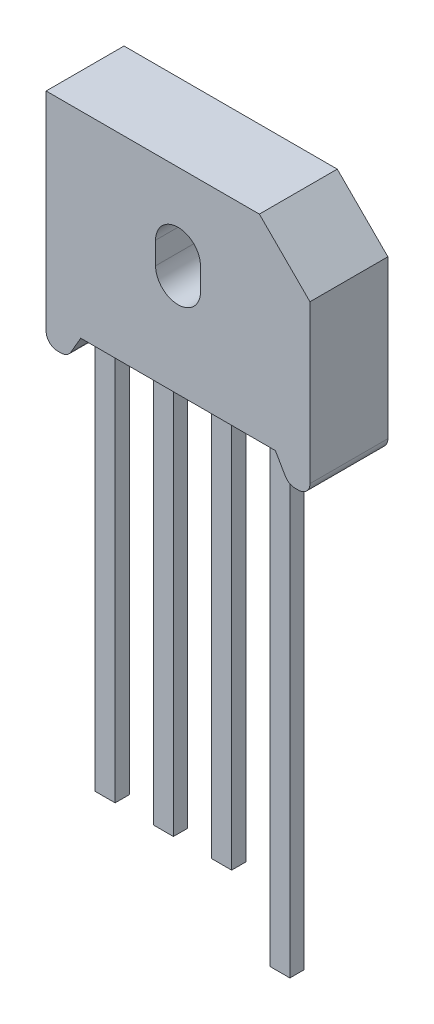
SolidWorks part; units mm, degrees
ref_plane "Front Plane" through (0, 0, 0) normal (0, 0, 1) x (1, 0, 0)
ref_plane "Top Plane" through (0, 0, 0) normal (0, 1, 0) x (1, 0, 0)
ref_plane "Right Plane" through (0, 0, 0) normal (1, 0, 0) x (0, 0, -1)
sketch "Sketch1" plane through (0, 0, 0) normal (0, 0, 1) x (1, 0, 0)
  line L0 (0, 47.902) -> (0, -49.3492) construction
  line L1 (-55.8616, 0) -> (48.9151, 0) construction
  line L2 (-11.6, 14.4039) -> (-11.6, -2.8961)
  line L6 (-11.6, 14.4039) -> (11.6, 14.4039)
  line L9 (11.6, 14.4039) -> (11.6, -2.8961)
  line L10 (7.15, 14.4039) -> (11.6, 9.9539)
  line L11 (0, 7.8539) -> (0, 5.9039) construction
  line L12 (1.975, 7.8539) -> (1.975, 5.9039)
  line L13 (-1.975, 7.8539) -> (-1.975, 5.9039)
  line L14 (-11.6, -2.8961) -> (-11.6, -3.8961)
  line L15 (-10.6, -4.8961) -> (-10.2891, -4.8961)
  line L16 (-9.4231, -4.3961) -> (-8.5588, -2.8991)
  line L17 (-8.5588, -2.8991) -> (8.5588, -2.8991)
  line L18 (11.6, -2.8961) -> (11.6, -3.8961)
  line L19 (10.6, -4.8961) -> (10.2891, -4.8961)
  line L20 (9.4231, -4.3961) -> (8.5588, -2.8991)
  arc A0 (1.975, 7.8539) -> (-1.975, 7.8539) centre (0, 7.8539) ccw
  arc A1 (-1.975, 5.9039) -> (1.975, 5.9039) centre (0, 5.9039) ccw
  arc A2 (9.4231, -4.3961) -> (10.2891, -4.8961) centre (10.2891, -3.8961) ccw
  arc A3 (-9.4231, -4.3961) -> (-10.2891, -4.8961) centre (-10.2891, -3.8961) cw
  arc A4 (-11.6, -3.8961) -> (-10.6, -4.8961) centre (-10.6, -3.8961) ccw
  arc A5 (11.6, -3.8961) -> (10.6, -4.8961) centre (10.6, -3.8961) cw
  point P7 (-8.564, -3.1175)
  point P12 (0, 14.4039)
  point P13 (0, -9.3053)
  point P19 (0, 6.8789)
  point P28 (0, -2.8991)
  point P30 (9.7118, -4.8961)
  point P33 (-9.7118, -4.8961)
  point P36 (-11.6, -4.8961)
  point P39 (11.6, -4.8961)
  point P40 (11.6, 10.1587)
  dimension "D8" = 1
  dimension "D9" = 1
  dimension "D1" = 23.2
  dimension "D2" = 3.95
  dimension "D3" = 1.95
  dimension "D4" = 17.3
  dimension "D5" = 19.3
  dimension "D6" = 240
  dimension "D7" = 10.8
  dimension "D10" = 4.45
  dimension "D11" = 135
extrude "Boss-Extrude1" add sketch "Sketch1" along normal mid plane 6.85 contours A5 L18 L9 L10 L6 L2 L14 A4 L15 A3 L16 L17 L20 A2 L19 A1 L13 A0 L12
sketch "Sketch2" plane through (0, -2.8991, 0) normal (0, -1, 0) x (1, 0, 0)
  line L0 (-7.9995, 1.525) -> (8.0463, 1.525) construction
  line L1 (-8.5588, -3.425) -> (8.5588, -3.425) construction
  line L2 (-8.5588, 0.9) -> (-6.8088, 0.9)
  line L3 (-8.5588, 0.9) -> (-8.5588, 2.15)
  line L4 (-8.5588, 2.15) -> (-6.8088, 2.15)
  line L5 (-6.8088, 0.9) -> (-6.8088, 2.15)
  line L6 (-8.5588, 0.9) -> (-6.8088, 2.15) construction
  line L7 (-8.5588, 2.15) -> (-6.8088, 0.9) construction
  line L8 (-8.5588, 3.425) -> (-8.5588, -3.425) construction
  line L9 (-3.4363, 0.9) -> (-3.4363, 2.15)
  line L10 (-3.4363, 0.9) -> (-1.6863, 0.9)
  line L11 (-1.6863, 0.9) -> (-1.6863, 2.15)
  line L12 (-3.4363, 2.15) -> (-1.6863, 2.15)
  line L13 (1.6863, 0.9) -> (1.6863, 2.15)
  line L14 (1.6863, 0.9) -> (3.4363, 0.9)
  line L15 (3.4363, 0.9) -> (3.4363, 2.15)
  line L16 (1.6863, 2.15) -> (3.4363, 2.15)
  line L17 (6.8088, 0.9) -> (6.8088, 2.15)
  line L18 (6.8088, 0.9) -> (8.5588, 0.9)
  line L19 (8.5588, 0.9) -> (8.5588, 2.15)
  line L20 (6.8088, 2.15) -> (8.5588, 2.15)
  line L21 (8.5588, 3.425) -> (8.5588, -3.425) construction
  point P3 (-7.6838, 1.525)
  dimension "D1" = 4.95
  dimension "D3" = 1.75
  dimension "D4" = 1.25
  dimension "D2" = 4
extrude "Boss-Extrude2" add sketch "Sketch2" along normal blind 35.15
sketch "Sketch3" plane through (0, -38.0491, 0) normal (0, -1, 0) x (1, 0, 0)
  line L0 (6.8088, 0.9) -> (8.5588, 0.9) construction
  line L1 (6.8088, 0.9) -> (8.5588, 0.9)
  line L2 (6.8088, 0.9) -> (6.8088, 2.15)
  line L3 (6.8088, 2.15) -> (8.5588, 2.15)
  line L4 (8.5588, 0.9) -> (8.5588, 2.15)
  line L5 (6.8088, 0.9) -> (8.5588, 2.15) construction
  line L6 (6.8088, 2.15) -> (8.5588, 0.9) construction
  line L7 (6.8088, 2.15) -> (6.8088, 0.9) construction
  point P0 (7.6838, 1.525)
extrude "Boss-Extrude3" add sketch "Sketch3" along normal blind 5.65
